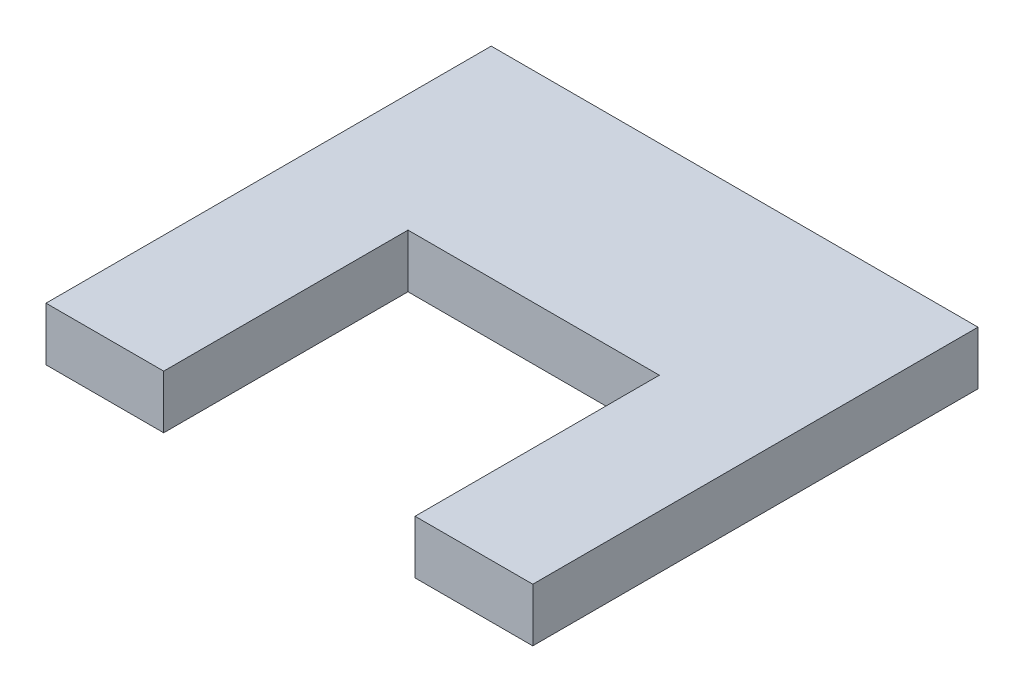
SolidWorks part; units mm, degrees
ref_plane "Front Plane" through (0, 0, 0) normal (0, 0, 1) x (1, 0, 0)
ref_plane "Top Plane" through (0, 0, 0) normal (0, 1, 0) x (1, 0, 0)
ref_plane "Right Plane" through (0, 0, 0) normal (1, 0, 0) x (0, 0, -1)
sketch "Sketch1" plane through (0, 0, 0) normal (0, 1, 0) x (1, 0, 0)
  line L1 (-41, 37.5) -> (41, 37.5)
  line L2 (-41, 37.5) -> (-41, -37.5)
  line L3 (-41, -37.5) -> (41, -37.5)
  line L4 (41, 37.5) -> (41, -37.5)
  line L5 (-41, 37.5) -> (41, -37.5) construction
  line L6 (-41, -37.5) -> (41, 37.5) construction
  line L7 (-41, 37.5) -> (-21.17, 37.5)
  line L8 (-41, 37.5) -> (-41, -37.5)
  line L9 (-41, -37.5) -> (-21.17, -37.5)
  line L10 (-21.17, 37.5) -> (-21.17, -37.5)
  line L11 (41, 37.5) -> (21.17, 37.5)
  line L12 (41, 37.5) -> (41, -37.5)
  line L13 (41, -37.5) -> (21.17, -37.5)
  line L14 (21.17, 37.5) -> (21.17, -37.5)
  line L15 (-41, 37.5) -> (41, 37.5)
  line L16 (-41, 37.5) -> (-41, 3.65)
  line L17 (-41, 3.65) -> (41, 3.65)
  line L18 (41, 37.5) -> (41, 3.65)
  point P0 (0, 0)
  dimension "D1" = 82
  dimension "D2" = 75
  dimension "D3" = 19.83
  dimension "D4" = 19.83
  dimension "D5" = 33.85
extrude "Boss-Extrude1" add sketch "Sketch1" along normal blind 9 contours L17 L8 L3 L10 | L2 L17 L10 L1 | L10 L17 L14 L1 | L14 L17 L4 L1 | L17 L14 L3 L12
